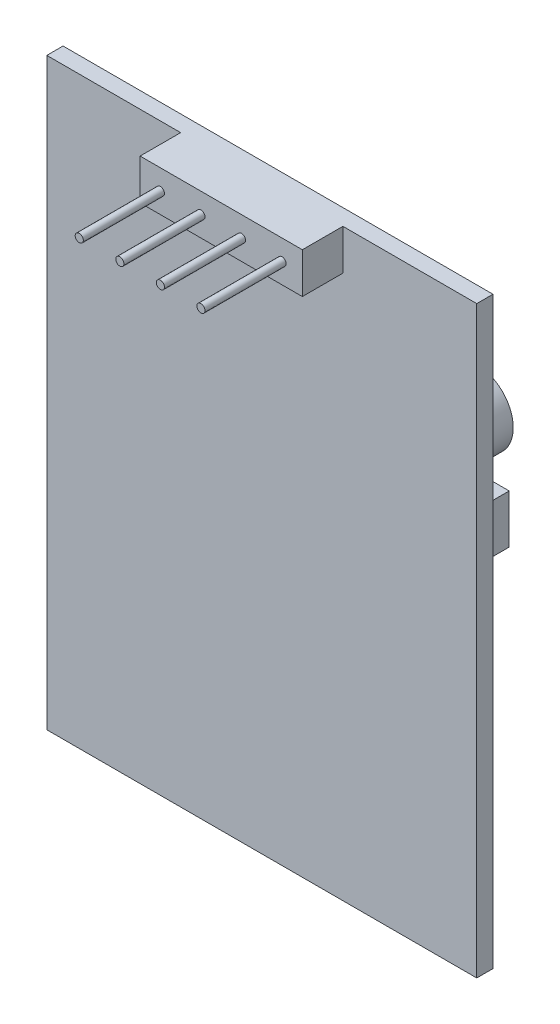
SolidWorks part; units mm, degrees
ref_plane "Plan de face" through (0, 0, 0) normal (0, 0, 1) x (1, 0, 0)
ref_plane "Plan de dessus" through (0, 0, 0) normal (0, 1, 0) x (1, 0, 0)
ref_plane "Plan de droite" through (0, 0, 0) normal (1, 0, 0) x (0, 0, -1)
sketch "Esquisse1" plane through (0, 0, 0) normal (0, 0, 1) x (1, 0, 0)
  line L1 (0, 0) -> (-26.5, 0)
  line L2 (0, 0) -> (0, 36)
  line L3 (0, 36) -> (-26.5, 36)
  line L4 (-26.5, 0) -> (-26.5, 36)
  dimension "D1" = 26.5
  dimension "D2" = 36
extrude "Boss.-Extru.1" add sketch "Esquisse1" along normal blind 1
sketch "Esquisse2" plane through (0, 0, 1) normal (0, 0, 1) x (1, 0, 0)
  line L0 (-13.25, 36) -> (-18.25, 36) construction
  line L1 (0, 36) -> (-26.5, 36) construction
  line L2 (-13.25, 36) -> (-8.25, 36) construction
  line L4 (-18.25, 36) -> (-8.25, 36)
  line L5 (-18.25, 36) -> (-18.25, 33.5)
  line L6 (-18.25, 33.5) -> (-8.25, 33.5)
  line L7 (-8.25, 36) -> (-8.25, 33.5)
  dimension "D1" = 5
  dimension "D2" = 5
  dimension "D3" = 2.5
extrude "Boss.-Extru.2" add sketch "Esquisse2" along normal blind 2.5
sketch "Esquisse3" plane through (0, 0, 3.5) normal (0, 0, 1) x (1, 0, 0)
  line L0 (-18.25, 34.75) -> (-17, 34.75) construction
  line L1 (-18.25, 36) -> (-18.25, 33.5) construction
  line L2 (-17, 34.75) -> (-9.332, 34.75) construction
  line L3 (-9.332, 34.75) -> (-8.25, 34.75) construction
  line L4 (-8.25, 33.5) -> (-8.25, 36) construction
  circle A0 centre (-17, 34.75) radius 0.25
  circle A1 centre (-14.5, 34.75) radius 0.25
  circle A2 centre (-12, 34.75) radius 0.25
  circle A3 centre (-9.5, 34.75) radius 0.25
  dimension "D2" = 0.5
  dimension "D1" = 1.25
  dimension "D3" = 4
extrude "Boss.-Extru.3" add sketch "Esquisse3" along normal blind 5 and the other way blind 4
sketch "Esquisse4" plane through (0, 0, 0) normal (0, 0, -1) x (-1, 0, 0)
  line L0 (0, 31.3112) -> (25.7671, 31.3112) construction
  line L1 (0, 0) -> (0, 36) construction
  line L3 (6.8, 29.8112) -> (7.8, 29.8112)
  line L4 (6.8, 29.8112) -> (6.8, 32.8112)
  line L5 (6.8, 32.8112) -> (7.8, 32.8112)
  line L6 (7.8, 29.8112) -> (7.8, 32.8112)
  line L7 (6.8, 29.8112) -> (7.8, 32.8112) construction
  line L8 (6.8, 32.8112) -> (7.8, 29.8112) construction
  line L9 (8.8, 30.3112) -> (9.8, 30.3112)
  line L10 (8.8, 30.3112) -> (8.8, 32.3112)
  line L11 (8.8, 32.3112) -> (9.8, 32.3112)
  line L12 (9.8, 30.3112) -> (9.8, 32.3112)
  line L13 (8.8, 30.3112) -> (9.8, 32.3112) construction
  line L14 (8.8, 32.3112) -> (9.8, 30.3112) construction
  line L15 (10.8, 30.3112) -> (11.8, 30.3112)
  line L16 (10.8, 30.3112) -> (10.8, 32.3112)
  line L17 (10.8, 32.3112) -> (11.8, 32.3112)
  line L18 (11.8, 30.3112) -> (11.8, 32.3112)
  line L19 (10.8, 30.3112) -> (11.8, 32.3112) construction
  line L20 (10.8, 32.3112) -> (11.8, 30.3112) construction
  line L21 (12.8, 30.5612) -> (13.3, 30.5612)
  line L22 (12.8, 30.5612) -> (12.8, 32.0612)
  line L23 (12.8, 32.0612) -> (13.3, 32.0612)
  line L24 (13.3, 30.5612) -> (13.3, 32.0612)
  line L25 (12.8, 30.5612) -> (13.3, 32.0612) construction
  line L26 (12.8, 32.0612) -> (13.3, 30.5612) construction
  line L27 (14.3, 30.3112) -> (15.8, 30.3112)
  line L28 (14.3, 30.3112) -> (14.3, 32.3112)
  line L29 (14.3, 32.3112) -> (15.8, 32.3112)
  line L30 (15.8, 30.3112) -> (15.8, 32.3112)
  line L31 (14.3, 30.3112) -> (15.8, 32.3112) construction
  line L32 (14.3, 32.3112) -> (15.8, 30.3112) construction
  line L33 (16.8, 30.8112) -> (17.3, 30.8112)
  line L34 (16.8, 30.8112) -> (16.8, 31.8112)
  line L35 (16.8, 31.8112) -> (17.3, 31.8112)
  line L36 (17.3, 30.8112) -> (17.3, 31.8112)
  line L37 (16.8, 30.8112) -> (17.3, 31.8112) construction
  line L38 (16.8, 31.8112) -> (17.3, 30.8112) construction
  point P4 (7.3, 31.3112)
  point P9 (9.3, 31.3112)
  point P14 (11.3, 31.3112)
  point P19 (13.05, 31.3112)
  point P24 (15.05, 31.3112)
  point P29 (17.05, 31.3112)
  dimension "D1" = 1
  dimension "D2" = 1
  dimension "D3" = 1
  dimension "D4" = 1
  dimension "D5" = 1
  dimension "D6" = 1
  dimension "D7" = 1
  dimension "D8" = 1
  dimension "D9" = 0.5
  dimension "D10" = 1.5
  dimension "D11" = 0.5
  dimension "D12" = 1
  dimension "D13" = 2
  dimension "D14" = 1.5
  dimension "D15" = 2
  dimension "D16" = 2
  dimension "D17" = 3
  dimension "D18" = 6.8
extrude "Boss.-Extru.4" add sketch "Esquisse4" along normal blind 0.5
sketch "Esquisse5" plane through (0, 0, 0) normal (0, 0, -1) x (-1, 0, 0)
  line L0 (0, 0) -> (0, 36) construction
  line L1 (0, 36) -> (26.5, 36) construction
  circle A0 centre (3, 27.5) radius 2
  dimension "D2" = 4
  dimension "D1" = 3
  dimension "D3" = 8.5
extrude "Boss.-Extru.5" add sketch "Esquisse5" along normal blind 0.5
sketch "Esquisse6" plane through (0, 0, -0.5) normal (0, 0, -1) x (-1, 0, 0)
  circle A0 centre (3, 27.5) radius 2.25
  dimension "D1" = 4.5
extrude "Boss.-Extru.6" add sketch "Esquisse6" along normal blind 1.5
sketch "Esquisse7" plane through (0, 0, 0) normal (0, 0, -1) x (-1, 0, 0)
  line L0 (0, 0) -> (0, 36) construction
  line L1 (5.5, 22.1) -> (20.5, 22.1)
  line L2 (5.5, 22.1) -> (5.5, 10.5)
  line L3 (5.5, 10.5) -> (20.5, 10.5)
  line L4 (20.5, 22.1) -> (20.5, 10.5)
  line L5 (1, 24) -> (3, 24)
  line L6 (1, 24) -> (1, 21)
  line L7 (1, 21) -> (3, 21)
  line L8 (3, 24) -> (3, 21)
  line L9 (26.5, 0) -> (0, 0) construction
  circle A0 centre (3, 27.5) radius 2.25 construction
  dimension "D1" = 2
  dimension "D2" = 3
  dimension "D3" = 1
  dimension "D4" = 3.5
  dimension "D5" = 2.5
  dimension "D6" = 15
  dimension "D7" = 11.6
  dimension "D8" = 10.5
extrude "Boss.-Extru.7" add sketch "Esquisse7" along normal blind 2
sketch "Esquisse8" plane through (0, 0, 0) normal (0, 0, -1) x (-1, 0, 0)
  line L1 (3.6406, 23.1872) -> (4.2143, 23.1872)
  line L2 (3.6406, 23.1872) -> (3.6406, 21.6095)
  line L3 (3.6406, 21.6095) -> (4.2143, 21.6095)
  line L4 (4.2143, 23.1872) -> (4.2143, 21.6095)
  line L5 (1.1546, 8.5) -> (1.6546, 8.5)
  line L6 (1.1546, 8.5) -> (1.1546, 7)
  line L7 (1.1546, 7) -> (1.6546, 7)
  line L8 (1.6546, 8.5) -> (1.6546, 7)
  line L9 (2.6366, 8.5) -> (3.1366, 8.5)
  line L10 (2.6366, 8.5) -> (2.6366, 7)
  line L11 (2.6366, 7) -> (3.1366, 7)
  line L12 (3.1366, 8.5) -> (3.1366, 7)
  line L13 (15, 8) -> (15.5, 8)
  line L14 (15, 8) -> (15, 6.5)
  line L15 (15, 6.5) -> (15.5, 6.5)
  line L16 (15.5, 8) -> (15.5, 6.5)
  line L17 (16.2, 7) -> (19.2, 7)
  line L18 (16.2, 7) -> (16.2, 6)
  line L19 (16.2, 6) -> (19.2, 6)
  line L20 (19.2, 7) -> (19.2, 6)
  line L21 (26.5, 0) -> (0, 0) construction
  line L22 (26.5, 36) -> (26.5, 0) construction
  circle A0 centre (17.5, 3) radius 1.2
  circle A1 centre (17.5, 3) radius 1.05
  point P27 (0, 0)
  point P30 (26.5, 1.8353)
  dimension "D17" = 2.4
  dimension "D18" = 2.1
  dimension "D1" = 0.5
  dimension "D2" = 0.5
  dimension "D3" = 1.5
  dimension "D4" = 1.5
  dimension "D5" = 7
  dimension "D6" = 7
  dimension "D7" = 6
  dimension "D8" = 6.5
  dimension "D9" = 0.5
  dimension "D10" = 1
  dimension "D11" = 3
  dimension "D12" = 1.5
  dimension "D13" = 7.3
  dimension "D14" = 11
  dimension "D15" = 3
  dimension "D16" = 9
extrude "Boss.-Extru.8" add sketch "Esquisse8" along normal blind 0.5
